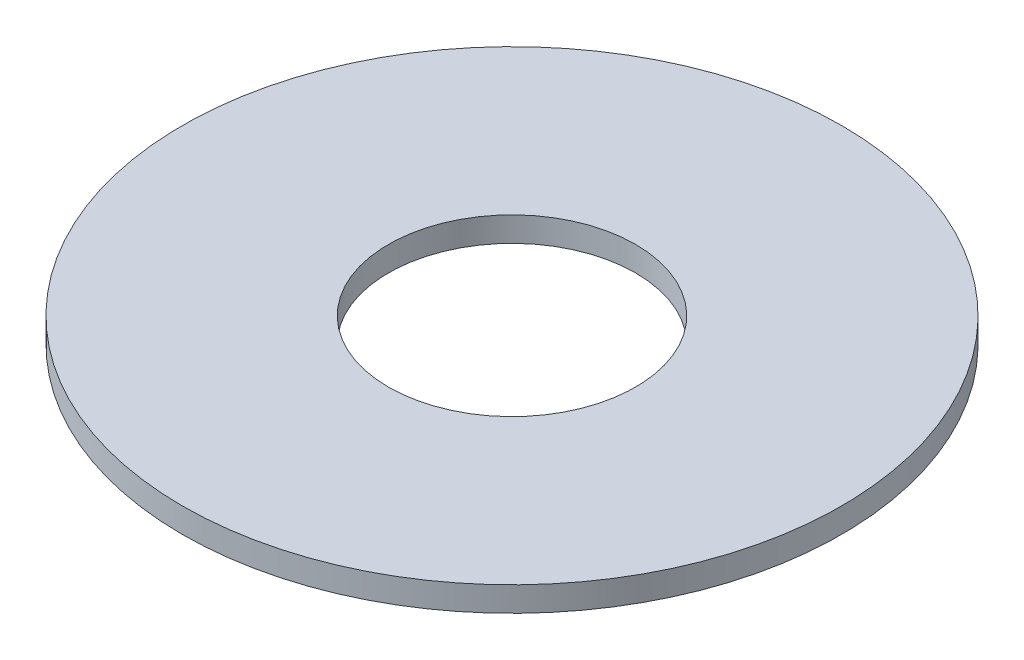
SolidWorks part; units mm, degrees
ref_plane "Alzado" through (0, 0, 0) normal (0, 0, 1) x (1, 0, 0)
ref_plane "Planta" through (0, 0, 0) normal (0, 1, 0) x (1, 0, 0)
ref_plane "Vista lateral" through (0, 0, 0) normal (1, 0, 0) x (0, 0, -1)
sketch "Croquis1" plane through (0, 0, 0) normal (0, 1, 0) x (1, 0, 0)
  circle A0 centre (0, 0) radius 1.5
  circle A1 centre (0, 0) radius 4
  dimension "D1" = 3
  dimension "D2" = 8
extrude "Saliente-Extruir1" add sketch "Croquis1" along normal blind 0.3
